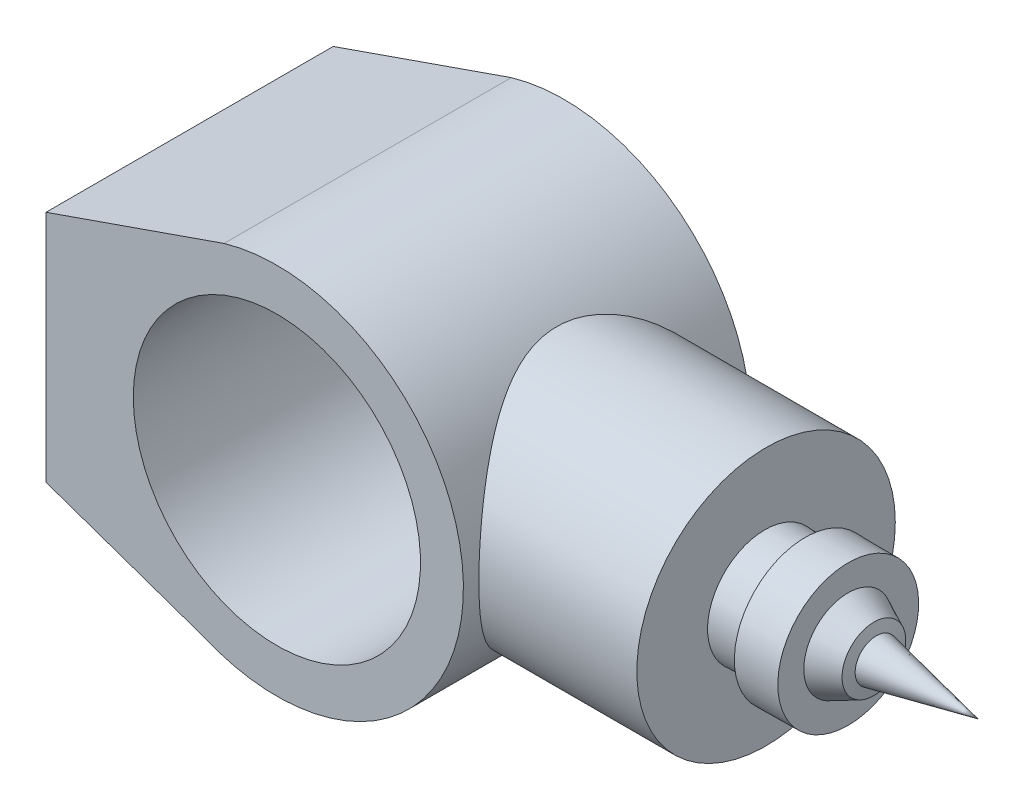
SolidWorks part; units mm, degrees
ref_plane "Front Plane" through (0, 0, 0) normal (0, 0, 1) x (1, 0, 0)
ref_plane "Top Plane" through (0, 0, 0) normal (0, 1, 0) x (1, 0, 0)
ref_plane "Right Plane" through (0, 0, 0) normal (1, 0, 0) x (0, 0, -1)
sketch "Sketch1" plane through (0, 0, 0) normal (0, 0, 1) x (1, 0, 0)
  line L0 (-80.3328, 40.8167) -> (-18.3273, 62.4204)
  line L1 (-80.3312, -40.5944) -> (-80.3328, 40.8167)
  line L2 (-80.3312, -40.5944) -> (-25.7188, -59.6333)
  arc A0 (-25.7188, -59.6333) -> (-18.3273, 62.4204) centre (0.0062, 0.0595) ccw
  circle A1 centre (0.0595, 0.333) radius 50
  point P1 (-80.3328, 40.9449)
  point P4 (-80.3612, -40.584)
  dimension "D1" = 130
  dimension "D2" = 100
extrude "Boss-Extrude1" add sketch "Sketch1" along normal mid plane 100
ref_plane "Plane1" through (120, 0, 0) normal (1, 0, 0) x (0, 0, -1)
sketch "Sketch2" plane through (120, 0, 0) normal (1, 0, 0) x (0, 0, -1)
  circle A0 centre (0.3806, -0.1308) radius 45
  dimension "D1" = 90
extrude "Boss-Extrude2" add sketch "Sketch2" against normal up to next
sketch "Sketch4" plane through (0, 0, 0) normal (0, 0, 1) x (1, 0, 0)
  line L0 (119.9993, 0.2833) -> (194.1731, 0.2943)
  line L1 (119.9993, 0.2833) -> (119.9943, -19.7005)
  line L2 (119.9943, -19.7005) -> (133.9943, -19.3694)
  line L3 (133.9943, -19.3694) -> (133.9981, -24.3694)
  line L4 (133.9981, -24.3694) -> (148.9981, -24.2323)
  line L5 (148.9981, -24.2323) -> (148.8915, -15.0807)
  line L6 (148.8915, -15.0807) -> (157.9289, -10.7999)
  line L7 (157.9289, -10.7999) -> (158.7792, -7.0898)
  line L8 (158.7792, -7.0898) -> (194.1731, 0.2943)
  point P11 (119.9215, 0.16)
  point P12 (121.6125, 0.4815)
  point P13 (135.0932, -19.196)
  point P14 (134.0183, -19.2678)
  point P15 (134.0317, -24.3694)
  point P16 (148.9981, -24.2323)
  point P17 (207.333, 0.2962)
  point P18 (149.0476, -24.2158)
  point P19 (194.0399, 0.4666)
  point P20 (119.9943, -19.5211)
  point P21 (119.9993, 0.2995)
revolve "Revolve1" add sketch "Sketch4" angle 360 about L0
